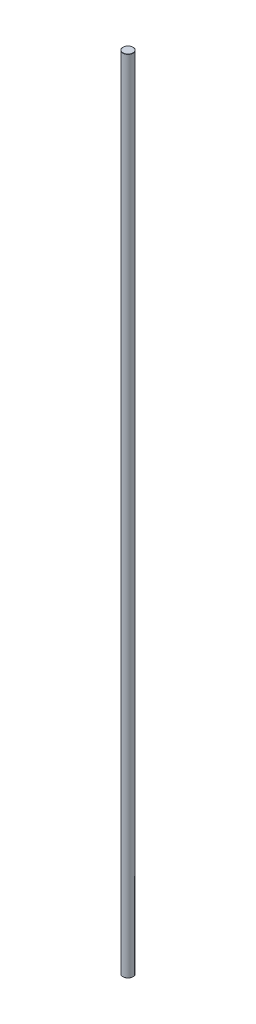
SolidWorks part; units mm, degrees
material "Plain Carbon Steel"
ref_plane "Front Plane" through (0, 0, 0) normal (0, 0, 1) x (1, 0, 0)
ref_plane "Top Plane" through (0, 0, 0) normal (0, 1, 0) x (1, 0, 0)
ref_plane "Right Plane" through (0, 0, 0) normal (1, 0, 0) x (0, 0, -1)
sketch "Sketch1" plane through (0, 0, 0) normal (0, 1, 0) x (1, 0, 0)
  circle A0 centre (0, 0) radius 6.35
  dimension "D1" = 12.7
extrude "Boss-Extrude1" add sketch "Sketch1" along normal mid plane 990.6
chamfer "Chamfer1" distance 0.254 angle 45 2 edges at (0, -495.3, 6.35) (0, 495.3, 6.35)
